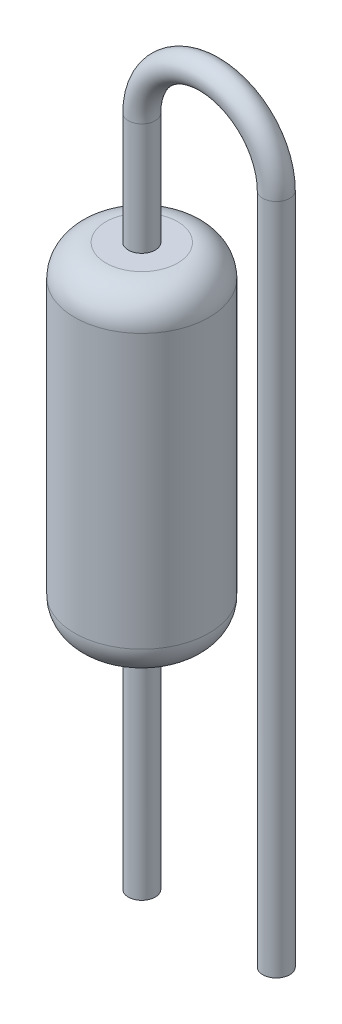
SolidWorks part; units mm, degrees
ref_plane "Спереди" through (0, 0, 0) normal (0, 0, 1) x (1, 0, 0)
ref_plane "Сверху" through (0, 0, 0) normal (0, 1, 0) x (1, 0, 0)
ref_plane "Справа" through (0, 0, 0) normal (1, 0, 0) x (0, 0, -1)
sketch "Эскиз1" plane through (0, 0, 0) normal (0, 0, 1) x (1, 0, 0)
  line L0 (-31.2904, 0) -> (32.9593, 0) construction
  line L1 (0, 0) -> (0, 15)
  line L2 (3, 15) -> (3, 0)
  arc A0 (0, 15) -> (3, 15) centre (1.5, 15) cw
  dimension "D1" = 1.5
  dimension "D2" = 15
sketch "Эскиз2" plane through (0, 0, 0) normal (0, 1, 0) x (1, 0, 0)
  circle A0 centre (0, 0) radius 0.3
  dimension "D1" = 0.6
sweep "По траектории1" add profiles "Эскиз2" path "Эскиз1"
ref_plane "Плоскость1" through (0, 5, 0) normal (0, -1, 0) x (1, 0, 0)
sketch "Эскиз3" plane through (0, 5, 0) normal (0, -1, 0) x (1, 0, 0)
  circle A0 centre (0, 0) radius 1.5
  dimension "D1" = 3
extrude "Вытянуть1" add sketch "Эскиз3" against normal blind 7.5
fillet "Скругление1" radius 0.7 2 edges at (0, 12.5, -1.5) (0, 5, -1.5)
